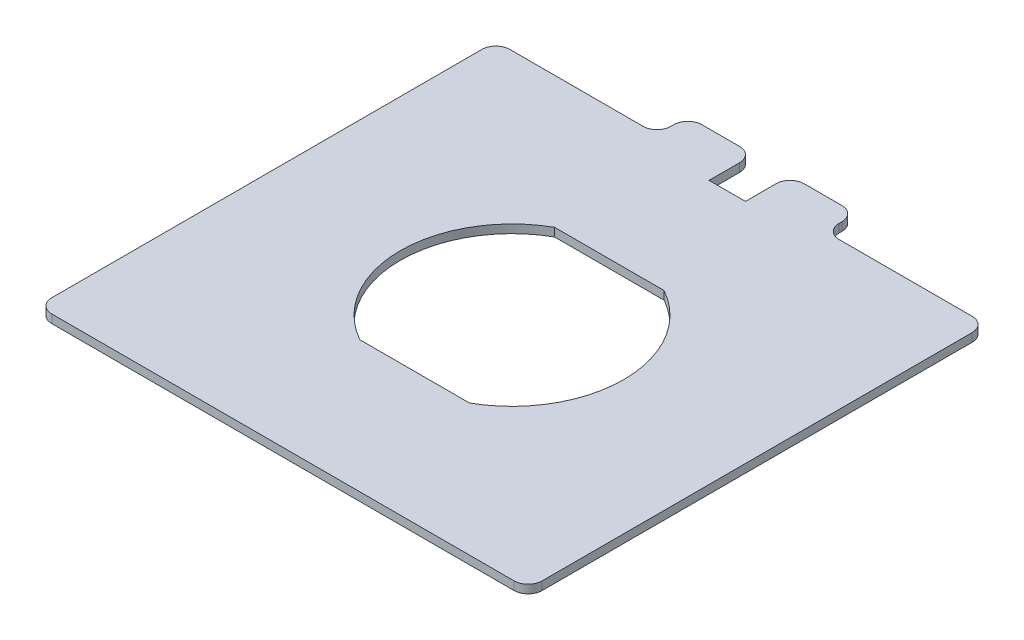
SolidWorks part; units mm, degrees
ref_plane "Front Plane" through (0, 0, 0) normal (0, 0, 1) x (1, 0, 0)
ref_plane "Top Plane" through (0, 0, 0) normal (0, 1, 0) x (1, 0, 0)
ref_plane "Right Plane" through (0, 0, 0) normal (1, 0, 0) x (0, 0, -1)
sketch "Esquisse1" plane through (0, 0, 0) normal (0, 1, 0) x (1, 0, 0)
  line L0 (7, 16.35) -> (39.5, 16.35)
  line L1 (-3.8718, 6.8) -> (3.8718, 6.8)
  line L3 (-3.8718, -6.8) -> (3.8718, -6.8)
  line L5 (-7.158, 3.1613) -> (7.158, -3.1613) construction
  line L6 (-7.158, -3.1613) -> (7.158, 3.1613) construction
  line L7 (-39.5, 16.35) -> (-7, 16.35)
  line L8 (-42.5, 13.35) -> (-42.5, -13.35)
  line L9 (-39.5, -16.35) -> (39.5, -16.35)
  line L10 (42.5, 13.35) -> (42.5, -13.35)
  line L11 (-42.5, 16.35) -> (42.5, -16.35) construction
  line L12 (-42.5, -16.35) -> (42.5, 16.35) construction
  line L13 (-5, 18.55) -> (-2.3, 18.55)
  line L14 (-6, 17.55) -> (-6, 17.35)
  line L16 (6, 17.55) -> (6, 17.35)
  line L17 (-6, 18.55) -> (0, 16.35) construction
  line L18 (0, 16.35) -> (6, 18.55) construction
  line L19 (2.3, 18.55) -> (5, 18.55)
  line L21 (-1.3, 17.55) -> (-1.3, 15.363)
  line L22 (-1.3, 15.363) -> (1.3, 15.363)
  line L23 (1.3, 17.55) -> (1.3, 15.363)
  line L24 (0, 18.55) -> (1.3, 15.363) construction
  line L25 (-1.3, 15.363) -> (0, 18.55) construction
  arc A0 (-3.8718, 6.8) -> (-3.8718, -6.8) centre (0, 0) ccw
  arc A1 (3.8718, -6.8) -> (3.8718, 6.8) centre (0, 0) ccw
  arc A2 (-42.5, -13.35) -> (-39.5, -16.35) centre (-39.5, -13.35) ccw
  arc A3 (39.5, -16.35) -> (42.5, -13.35) centre (39.5, -13.35) ccw
  arc A4 (39.5, 16.35) -> (42.5, 13.35) centre (39.5, 13.35) cw
  arc A5 (-39.5, 16.35) -> (-42.5, 13.35) centre (-39.5, 13.35) ccw
  arc A6 (-5, 18.55) -> (-6, 17.55) centre (-5, 17.55) ccw
  arc A7 (5, 18.55) -> (6, 17.55) centre (5, 17.55) cw
  arc A8 (6, 17.35) -> (7, 16.35) centre (7, 17.35) ccw
  arc A9 (-6, 17.35) -> (-7, 16.35) centre (-7, 17.35) cw
  arc A10 (1.3, 17.55) -> (2.3, 18.55) centre (2.3, 17.55) cw
  arc A11 (-1.3, 17.55) -> (-2.3, 18.55) centre (-2.3, 17.55) ccw
  point P26 (0, 16.35)
  point P40 (6, 16.35)
  point P43 (0, 18.55)
  point P51 (1.3, 18.55)
  dimension "D1" = 13.6
  dimension "D2" = 15.65
  dimension "D6" = 3
  dimension "D9" = 1
  dimension "D10" = 1
  dimension "D3" = 7.7435
  dimension "D4" = 32.7
  dimension "D5" = 85
  dimension "D7" = 2.2
  dimension "D8" = 12
extrude "Boss.-Extru.1" add sketch "Esquisse1" along normal blind 0.6
sketch "Esquisse2" plane through (0, 0.6, 0) normal (0, 1, 0) x (1, 0, 0)
  line L1 (-17.5, 25.525) -> (17.5, 25.525)
  line L2 (-17.5, 25.525) -> (-17.5, -25.525)
  line L3 (-17.5, -25.525) -> (17.5, -25.525)
  line L4 (17.5, 25.525) -> (17.5, -25.525)
  line L5 (-17.5, 25.525) -> (17.5, -25.525) construction
  line L6 (-17.5, -25.525) -> (17.5, 25.525) construction
  line L7 (-59.9799, 46.6703) -> (57.9815, 46.6703)
  line L8 (-59.9799, 46.6703) -> (-59.9799, -44.4759)
  line L9 (-59.9799, -44.4759) -> (57.9815, -44.4759)
  line L10 (57.9815, 46.6703) -> (57.9815, -44.4759)
  point P0 (0, 0)
  dimension "D1" = 35
extrude "Enlèv. mat.-Extru.1" cut sketch "Esquisse2" against normal through all
fillet "Congé1" radius 1 4 edges at (-17.5, 0.3, 16.35) (17.5, 0.3, 16.35) (17.5, 0.3, -16.35) (-17.5, 0.3, -16.35)
sketch "Esquisse3" plane through (0, 0.6, 0) normal (0, 1, 0) x (1, 0, 0)
  line L16 (-3.9113, -6.95) -> (3.9113, -6.95)
  line L17 (3.9113, 6.95) -> (-3.9113, 6.95)
  line L18 (-3.9113, -6.95) -> (3.9113, -6.95)
  line L19 (3.9113, 6.95) -> (-3.9113, 6.95)
  arc A14 (-3.9113, 6.95) -> (-3.9113, -6.95) centre (0, 0) ccw
  arc A15 (3.9113, -6.95) -> (3.9113, 6.95) centre (0, 0) ccw
  arc A16 (-3.9113, 6.95) -> (-3.9113, -6.95) centre (0, 0) ccw
  arc A17 (3.9113, -6.95) -> (3.9113, 6.95) centre (0, 0) ccw
  dimension "D1" = 0.15
extrude "Enlèv. mat.-Extru.2" cut sketch "Esquisse3" against normal through all
